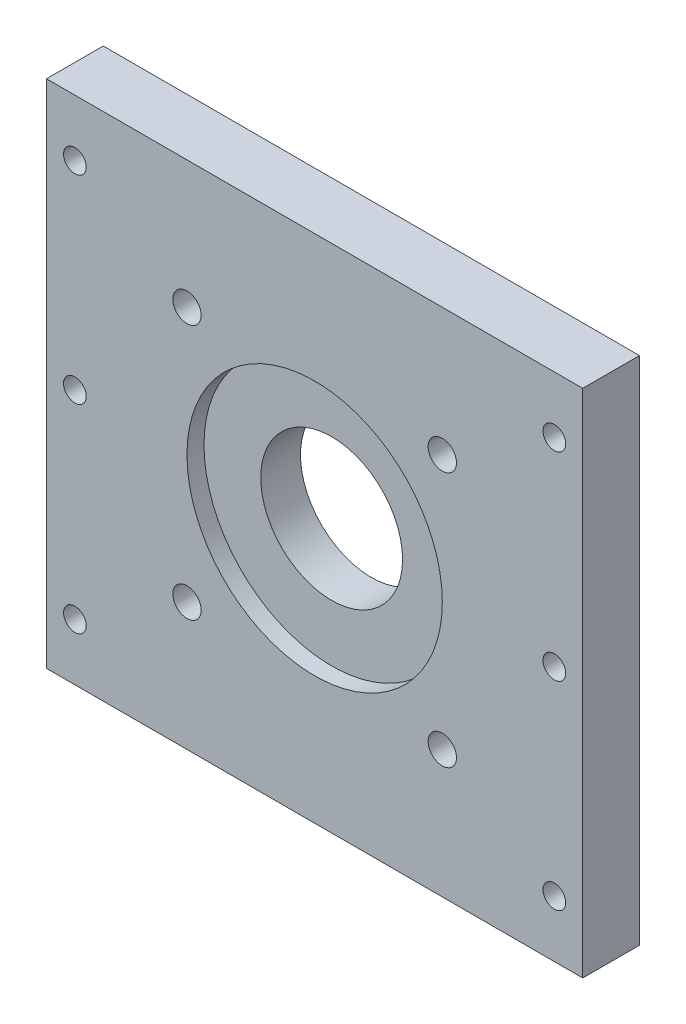
SolidWorks part; units mm, degrees
ref_plane "Front Plane" through (0, 0, 0) normal (0, 0, 1) x (1, 0, 0)
ref_plane "Top Plane" through (0, 0, 0) normal (0, 1, 0) x (1, 0, 0)
ref_plane "Right Plane" through (0, 0, 0) normal (1, 0, 0) x (0, 0, -1)
sketch "Sketch1" plane through (0, 0, 0) normal (0, 0, 1) x (1, 0, 0)
  line L8 (5, 90) -> (5, 0) construction
  line L13 (0, 0) -> (94.5, 0)
  line L14 (0, 0) -> (0, 90)
  line L15 (0, 90) -> (94.5, 90)
  line L16 (94.5, 0) -> (94.5, 90)
  line L17 (47.25, 90) -> (47.25, 0) construction
  line L18 (94.5, 45) -> (0, 45) construction
  line L19 (24.75, 67.5) -> (24.75, 22.5) construction
  line L20 (24.75, 22.5) -> (69.75, 22.5) construction
  line L21 (69.75, 22.5) -> (69.75, 67.5) construction
  line L22 (69.75, 67.5) -> (24.75, 67.5) construction
  line L23 (24.75, 22.5) -> (69.75, 67.5) construction
  circle A0 centre (5, 80) radius 2
  circle A1 centre (5, 45) radius 2
  circle A2 centre (5, 10) radius 2
  circle A3 centre (89.5, 10) radius 2
  circle A4 centre (89.5, 45) radius 2
  circle A5 centre (89.5, 80) radius 2
  circle A6 centre (24.75, 67.5) radius 2.5
  circle A7 centre (69.75, 67.5) radius 2.5
  circle A8 centre (69.75, 22.5) radius 2.5
  circle A9 centre (24.75, 22.5) radius 2.5
  circle A10 centre (47.25, 45) radius 12.5
  point P31 (47.25, 45)
  dimension "D4" = 4
  dimension "D5" = 5
  dimension "D8" = 10
  dimension "D9" = 25
  dimension "D1" = 90
  dimension "D2" = 94.5
  dimension "D3" = 5
  dimension "D6" = 45
  dimension "D7" = 45
extrude "Boss-Extrude1" add sketch "Sketch1" along normal blind 10
sketch "Sketch3" plane through (0, 0, 10) normal (0, 0, 1) x (1, 0, 0)
  circle A0 centre (47.25, 45) radius 15 construction
  circle A1 centre (47.25, 45) radius 12.5 construction
  circle A2 centre (47.25, 45) radius 22.5
  dimension "D1" = 7.5
  dimension "D2" = 30
extrude "Cut-Extrude2" cut sketch "Sketch3" against normal blind 3
